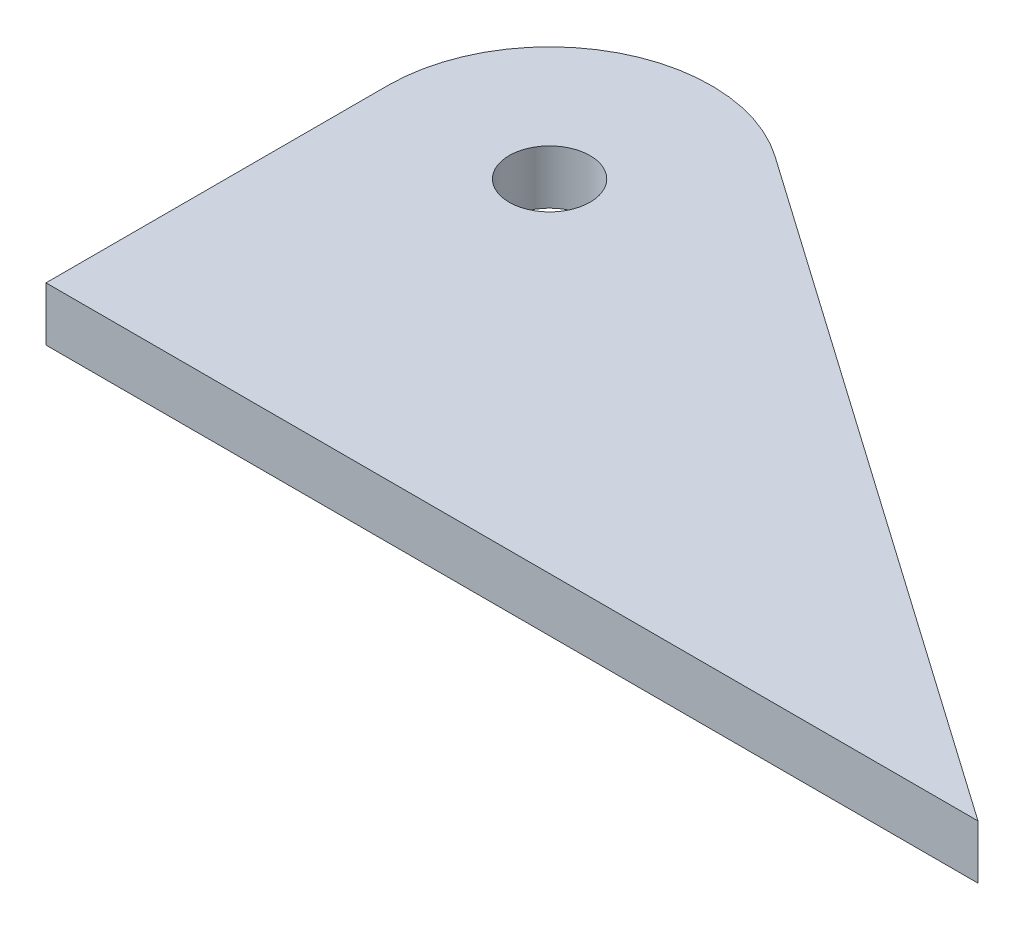
SolidWorks part; units mm, degrees
ref_plane "Front Plane" through (0, 0, 0) normal (0, 0, 1) x (1, 0, 0)
ref_plane "Top Plane" through (0, 0, 0) normal (0, 1, 0) x (1, 0, 0)
ref_plane "Right Plane" through (0, 0, 0) normal (1, 0, 0) x (0, 0, -1)
sketch "Sketch1" plane through (0, 0, 0) normal (0, 1, 0) x (1, 0, 0)
  line L0 (19.05, 63.5) -> (19.05, 0) construction
  line L5 (19.05, 0) -> (109.7374, 0)
  line L6 (109.7374, 0) -> (29.9766, 55.8491)
  line L7 (0, 0) -> (19.05, 0)
  line L8 (8.89, 24.1298) -> (8.89, 8.89)
  line L9 (0, 0) -> (0, 40.2442)
  line L10 (8.89, 8.89) -> (34.29, 8.89)
  line L11 (34.29, 8.89) -> (25.3453, 22.2645)
  line L12 (33.5725, 27.9154) -> (46.99, 8.89)
  line L13 (46.99, 8.89) -> (72.39, 8.89)
  line L14 (72.39, 8.89) -> (36.9441, 33.7095)
  arc A1 (29.9766, 55.8491) -> (0, 40.2442) centre (19.05, 40.2442) ccw
  circle A2 centre (19.05, 40.2442) radius 4.7625
  arc A3 (8.89, 24.1298) -> (25.3453, 22.2645) centre (19.05, 40.2442) ccw
  arc A4 (29.9766, 55.8491) -> (0, 40.2442) centre (19.05, 40.2442) ccw
  arc A5 (33.5725, 27.9154) -> (36.9441, 33.7095) centre (19.05, 40.2442) ccw
  dimension "D3" = 38.1
  dimension "D5" = 9.525
  dimension "D1" = 35
  dimension "D2" = 63.5
  dimension "D4" = 55.8491
  dimension "D6" = 8.89
  dimension "D7" = 8.89
  dimension "D8" = 35
  dimension "D9" = 25.4
  dimension "D10" = 8.89
  dimension "D11" = 12.7
  dimension "D12" = 25.4
extrude "Boss-Extrude2" add sketch "Sketch1" along normal blind 6.35 contours L0 A4 L9 L7 L10 L8 A3 A2 | A1 L0 A2 A3 L11 L10 L5 L6 L12 A5 L14 L13 | A3 L0 L10 L11 | L0 A3 L8 L10 | A5 L12 L13 L14
